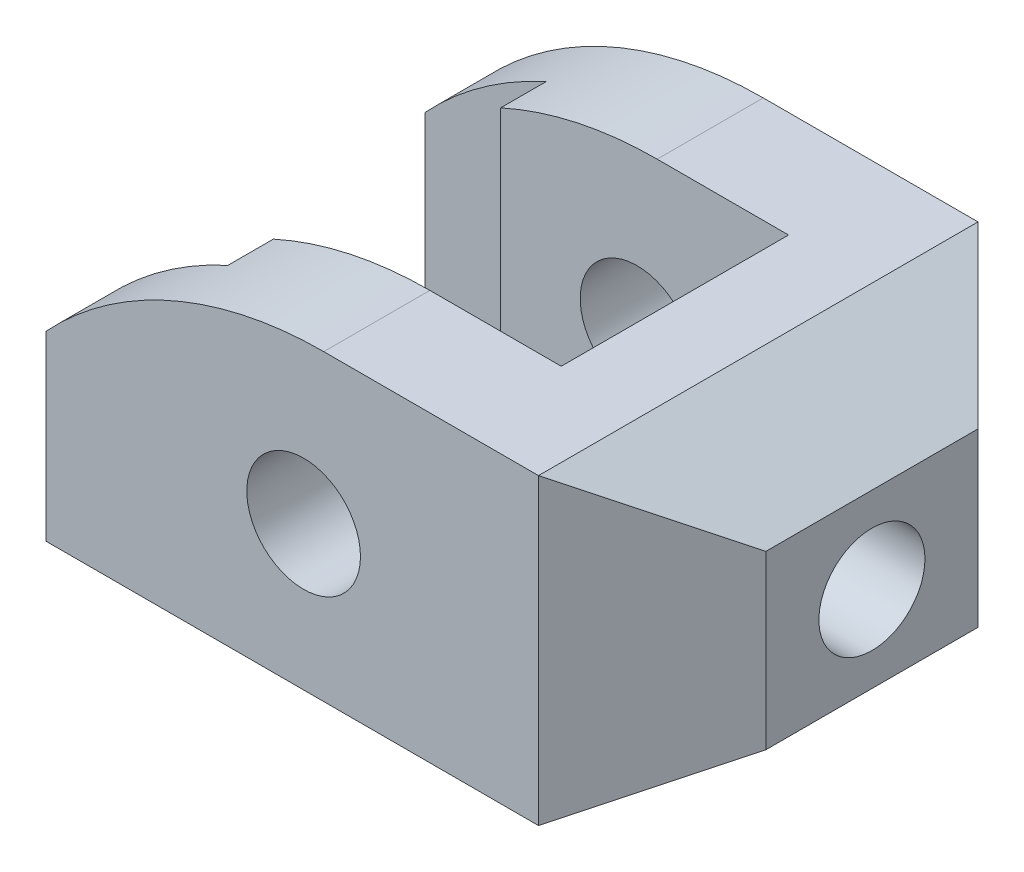
SolidWorks part; units mm, degrees
material "1060 Alloy"
ref_plane "Front Plane" through (0, 0, 0) normal (0, 0, 1) x (1, 0, 0)
ref_plane "Top Plane" through (0, 0, 0) normal (0, 1, 0) x (1, 0, 0)
ref_plane "Right Plane" through (0, 0, 0) normal (1, 0, 0) x (0, 0, -1)
sketch "Sketch1" plane through (0, 0, 0) normal (0, 1, 0) x (1, 0, 0)
  line L0 (0, 56.6723) -> (0, -56.6723) construction
  line L1 (-101.3253, 0) -> (101.3253, 0) construction
  line L3 (-40, 29) -> (40, 29)
  line L4 (-40, 29) -> (-40, -29)
  line L5 (-40, -29) -> (40, -29)
  line L6 (40, 29) -> (40, -29)
  line L7 (-40, 29) -> (40, -29) construction
  line L8 (-40, -29) -> (40, 29) construction
  point P0 (0, 0)
  point P4 (0, 0)
  point P8 (0, 0)
  dimension "D1" = 58
  dimension "D2" = 80
extrude "Boss-Extrude1" add sketch "Sketch1" along normal blind 40
sketch "Sketch2" plane through (0, 0, 29) normal (0, 0, 1) x (1, 0, 0)
  line L0 (-40, 0) -> (40, 0) construction
  line L1 (40, 40) -> (40, 0) construction
  line L2 (25, 0) -> (40, 0)
  line L3 (40, 0) -> (40, 8.6603)
  line L4 (40, 8.6603) -> (25, 0)
  line L5 (25, 40) -> (40, 40)
  line L6 (-40, 40) -> (40, 40) construction
  line L7 (40, 40) -> (40, 31.3397)
  line L8 (40, 31.3397) -> (25, 40)
  circle A0 centre (-6, 19) radius 7.5
  dimension "D1" = 19
  dimension "D3" = 15
  dimension "D2" = 46
  dimension "D4" = 15
  dimension "D5" = 30
  dimension "D6" = 15
  dimension "D7" = 30
extrude "Cut-Extrude1" cut sketch "Sketch2" against normal blind 95
sketch "Sketch4" plane through (0, 0, 29) normal (0, 0, 1) x (1, 0, 0)
  line L0 (-3.3394, 40) -> (-40, 40)
  line L1 (-40, 40) -> (-40, 24)
  line L2 (-40, 0) -> (-40, 24)
  line L3 (-40, 40) -> (-40, 0) construction
  line L4 (-40, 40) -> (25, 40) construction
  arc A1 (-3.3394, 40) -> (-40, 24) centre (-3.3394, -10) ccw
  line M5 (25, 40) -> (-40, 40)
  line M6 (-40, 40) -> (-40, 0)
  dimension "D1" = 24
  dimension "D2" = 100
extrude "Cut-Extrude4" cut sketch "Sketch4" against normal blind 95 contours A1 M5 M6
sketch "Sketch7" plane through (0, 40, 0) normal (0, 1, 0) x (1, 0, 0)
  line L0 (-47.3166, 0) -> (47.3166, 0) construction
  line L1 (25, 29) -> (25, -29)
  line L2 (25, 29) -> (40, 14)
  line L3 (40, 29) -> (40, -29) construction
  line L4 (40, 14) -> (40, 29)
  line L5 (40, 29) -> (25, 29)
  line L6 (25, -29) -> (40, -14)
  line L7 (40, -14) -> (40, -29)
  line L8 (40, -29) -> (25, -29)
  line L9 (14, 29) -> (14, -29)
  line L10 (25, 29) -> (-3.3394, 29) construction
  line L11 (-3.3394, -29) -> (25, -29) construction
  line L12 (-40, 15) -> (14, 15)
  line L13 (-40, 29) -> (-40, -29) construction
  line L14 (14, -15) -> (-40, -15)
  line L15 (-40, -29) -> (-3.3394, -29) construction
  line L16 (-3.3394, 29) -> (-40, 29) construction
  line L17 (-40, -15) -> (-40, 15)
  point P4 (0, 0)
  line M3 (-3.3394, 29) -> (-3.3394, -29)
  dimension "D1" = 45
  dimension "D2" = 45
  dimension "D3" = 11
  dimension "D4" = 14
  dimension "D5" = 14
  dimension "D6" = 14
extrude "Cut-Extrude5" cut sketch "Sketch7" against normal blind 95 contours L0 L17 L14 M3 | L17 L0 L12 M3 | L0 L9 L12 M3 | L0 L14 L9 M3 | L4 L5 L2 | L8 L7 L6
sketch "Sketch8" plane through (0, 40, 0) normal (0, 1, 0) x (1, 0, 0)
  line L0 (-40, 21) -> (-24, 21)
  line L1 (-40, 29) -> (-40, 15) construction
  line L2 (-24, 21) -> (-24, -21)
  line L3 (-24, -21) -> (-40, -21)
  line L4 (-40, -15) -> (-40, -29) construction
  line L5 (-40, -21) -> (-40, 21)
  line L6 (-40, -29) -> (-3.3394, -29) construction
  line L7 (-3.3394, 29) -> (-40, 29) construction
  dimension "D1" = 16
  dimension "D2" = 8
  dimension "D3" = 8
extrude "Cut-Extrude6" cut sketch "Sketch8" against normal blind 95
sketch "Sketch9" plane through (40, 0, 0) normal (1, 0, 0) x (0, 0, -1)
  line L0 (-29, 0) -> (-29, 40) construction
  line L2 (29, 0) -> (-29, 0) construction
  circle A0 centre (0, 20) radius 7
  dimension "D1" = 29
  dimension "D2" = 14
  dimension "D3" = 20
extrude "Cut-Extrude7" cut sketch "Sketch9" against normal blind 95
